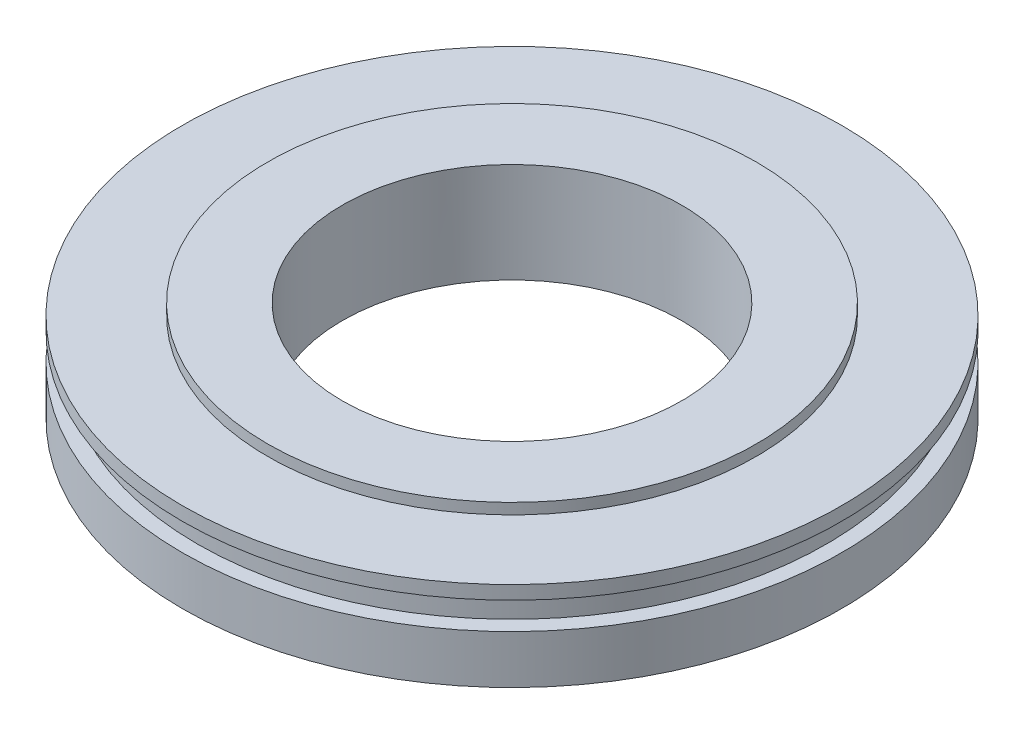
SolidWorks part; units mm, degrees
material "6061-T6 (SS)"
ref_plane "X-Y Datum" through (0, 0, 0) normal (0, 0, 1) x (1, 0, 0)
ref_plane "X-Z Datum" through (0, 0, 0) normal (0, 1, 0) x (1, 0, 0)
ref_plane "Y-Z Datum" through (0, 0, 0) normal (1, 0, 0) x (0, 0, -1)
sketch "Sketch1" plane through (0, 0, 0) normal (1, 0, 0) x (0, 0, -1)
  line L0 (-15.875, 2.6941) -> (-15.875, -5.0208)
  line L1 (-15.875, -5.0208) -> (-30.8407, -5.0208)
  line L3 (-30.8407, -1.0621) -> (-29.4348, -1.0621)
  line L4 (-29.4348, -1.0621) -> (-29.4348, 1.4779)
  line L5 (-29.4348, 1.4779) -> (-30.8407, 1.4779)
  line L6 (-30.8407, 1.4779) -> (-30.8407, 2.6941)
  line L7 (-30.8407, 2.6941) -> (-15.875, 2.6941)
  line L8 (0, 0) -> (0, -47872.0541) construction
  line L9 (0, 0) -> (-47872.0541, 0) construction
  line L10 (-30.8407, -1.0621) -> (-30.8407, -5.0208)
  line L11 (-14.7421, 2.6941) -> (15.0495, 2.6941) construction
  line L12 (-30.9994, 12.7) -> (-30.9994, -12.7) construction
  line L13 (14.2875, -5.0208) -> (-14.2875, -5.0208) construction
  line L14 (-29.3688, -1.0621) -> (29.3687, -1.0621) construction
  circle A0 centre (-30.3238, 0.2079) radius 0.889 construction
  point P15 (-30.9994, 0)
  point P16 (-29.4348, 0.2079)
  dimension "D3" = 1.778
  dimension "D1" = 31.75
  dimension "D2" = 61.6814
  dimension "D4" = 2.54
  dimension "D5" = 25.4
  dimension "D6" = 61.9989
  dimension "D7" = 1.5646
revolve "Revolve1" add sketch "Sketch1" angle 360 about L8
ref_plane "Plane1" through (0, 2.7479, 0) normal (0, -1, 0) x (-1, 0, 0)
sketch "Sketch3" plane through (0, 2.6941, 0) normal (0, 1, 0) x (1, 0, 0)
  circle A0 centre (0, 0) radius 30.8407
  circle A1 centre (0, 0) radius 15.875
  circle A2 centre (0, 0) radius 15.875 construction
  circle A3 centre (0, 0) radius 30.8407 construction
extrude "BandAid Solution thicker" add sketch "Sketch3" along normal up to surface (0.0538 mm away) up to plane "Plane1"
sketch "Sketch4" plane through (0, 2.7479, 0) normal (0, 1, 0) x (1, 0, 0)
  circle A0 centre (0, 0) radius 15.875
  circle A1 centre (0, 0) radius 22.86
  circle A2 centre (0, 0) radius 15.875 construction
  dimension "D1" = 45.72
extrude "Lip for Bearing" add sketch "Sketch4" along normal blind 1.016
sketch "Sketch5" plane through (0, -5.0208, 0) normal (0, -1, 0) x (1, 0, 0)
  circle A3 centre (0, 0) radius 15.875
  circle A4 centre (0, 0) radius 30.8407
  circle A5 centre (0, 0) radius 30.8407 construction
  circle A6 centre (0, 0) radius 15.875 construction
extrude "Boss-Extrude1" add sketch "Sketch5" along normal blind 0.5791
